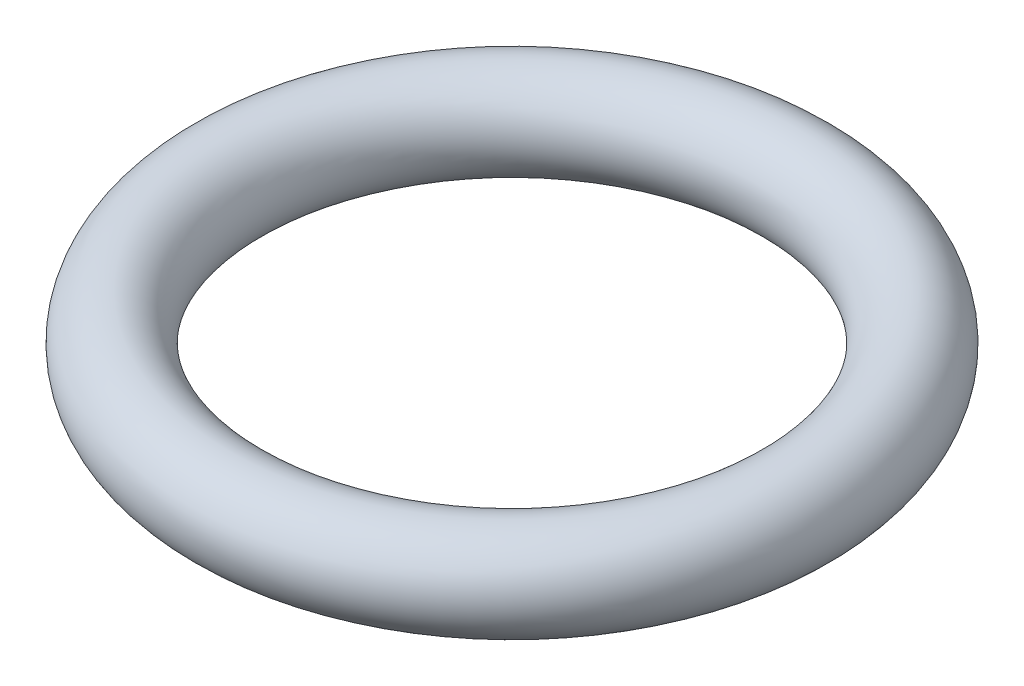
SolidWorks part; units mm, degrees
material "POLYURETHANE (11671)"
ref_plane "Front Plane" through (0, 0, 0) normal (0, 0, 1) x (1, 0, 0)
ref_plane "Top Plane" through (0, 0, 0) normal (0, 1, 0) x (1, 0, 0)
ref_plane "Right Plane" through (0, 0, 0) normal (1, 0, 0) x (0, 0, -1)
sketch "Sketch1" plane through (0, 0, 0) normal (0, 0, 1) x (1, 0, 0)
  line L0 (0, 33.3801) -> (0, -37.4109) construction
  circle A0 centre (15.25, 0) radius 2.5
  dimension "D2" = 5
  dimension "D1" = 15.25
revolve "Revolve1" add sketch "Sketch1" angle 360 about L0
equation "\"D1@Sketch1\"=20.5/2+5"
